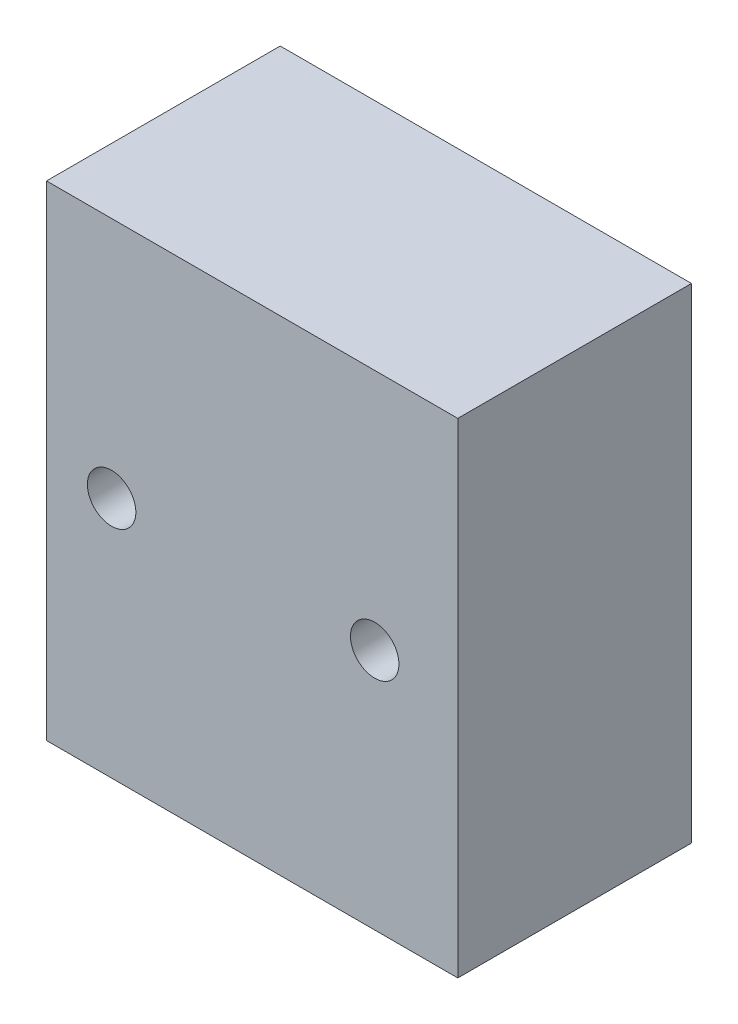
SolidWorks part; units mm, degrees
ref_plane "前基準面" through (0, 0, 0) normal (0, 0, 1) x (1, 0, 0)
ref_plane "上基準面" through (0, 0, 0) normal (0, 1, 0) x (1, 0, 0)
ref_plane "右基準面" through (0, 0, 0) normal (1, 0, 0) x (0, 0, -1)
sketch "草圖1" plane through (0, 0, 0) normal (0, 0, 1) x (1, 0, 0)
  line L1 (-14.85, 17.5) -> (14.85, 17.5)
  line L2 (-14.85, 17.5) -> (-14.85, -17.5)
  line L3 (-14.85, -17.5) -> (14.85, -17.5)
  line L4 (14.85, 17.5) -> (14.85, -17.5)
  line L5 (-14.85, 17.5) -> (14.85, -17.5) construction
  line L6 (-14.85, -17.5) -> (14.85, 17.5) construction
  point P0 (0, 0)
  dimension "D1" = 35
  dimension "D2" = 29.7
extrude "填料-伸長1" add sketch "草圖1" along normal blind 16.875 contours L1 L4 L3 L2
sketch "草圖2" plane through (0, 0, 0) normal (0, 0, -1) x (-1, 0, 0)
  circle A0 centre (-8.85, 0) radius 1.75
  circle A1 centre (10.15, 0) radius 1.75
extrude "除料-伸長1" cut sketch "草圖2" against normal blind 16.875
